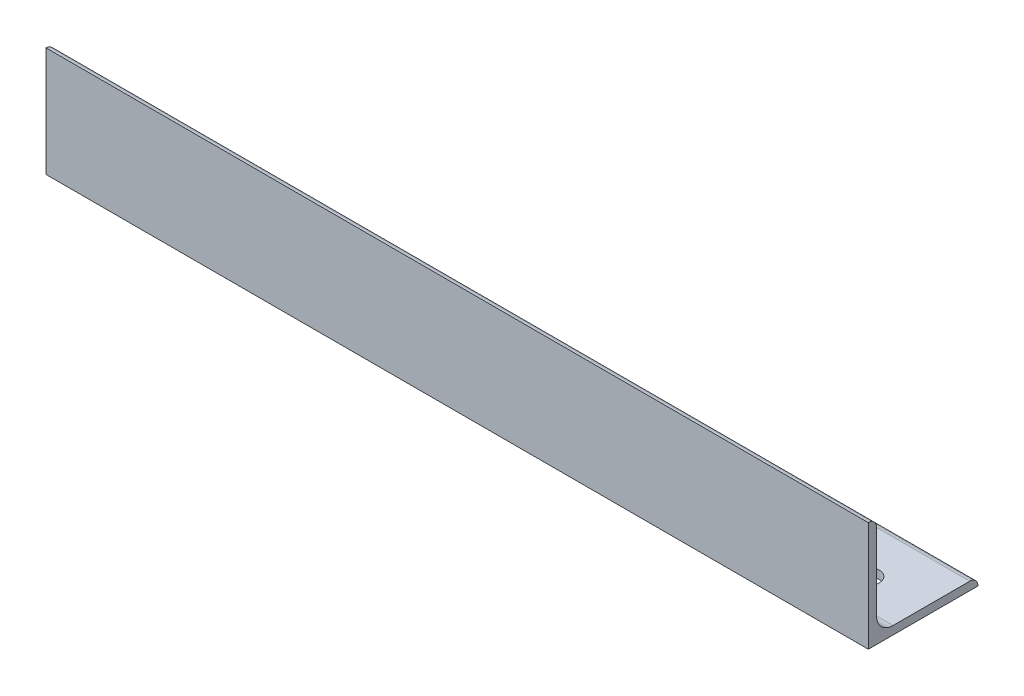
SolidWorks part; units mm, degrees
ref_plane "Front Plane" through (0, 0, 0) normal (0, 0, 1) x (1, 0, 0)
ref_plane "Top Plane" through (0, 0, 0) normal (0, 1, 0) x (1, 0, 0)
ref_plane "Right Plane" through (0, 0, 0) normal (1, 0, 0) x (0, 0, -1)
sketch "Sketch1" plane through (0, 0, 0) normal (0, 1, 0) x (1, 0, 0)
  line L0 (0, 0) -> (300, 0)
  dimension "D1" = 300
other "L angle (equal) 40X40X3(3)"
ref_plane "Plane1" through (0, 0, 0) normal (1, 0, 0) x (0, 0, -1)
sketch "Sketch13" plane through (0, 0, 0) normal (1, 0, 0) x (0, 0, -1)
  line L0 (0, 40) -> (0, 0)
  line L2 (3, 37) -> (3, 9)
  line L3 (9, 3) -> (37, 3)
  line L5 (40, 0) -> (0, 0)
  arc A0 (3, 37) -> (0, 40) centre (0, 37) ccw
  arc A1 (40, 0) -> (37, 3) centre (37, 0) ccw
  arc A2 (9, 3) -> (3, 9) centre (9, 9) cw
  point P8 (0, 20)
  point P9 (20, 0)
  point P10 (0, 0)
  dimension "Radius_2" = 3
  dimension "Radius_1" = 6
  dimension "V_leg" = 40
  dimension "H_leg" = 40
  dimension "thickness" = 3
ref_plane "Plane2" through (0, 0, 0) normal (0, -1, 0) x (-1, 0, 0)
sketch "Sketch14" plane through (0, 0, 0) normal (0, -1, 0) x (-1, 0, 0)
  line L0 (-280, 40) -> (-280, 0) construction
  line L1 (-20, 0) -> (-20, 40) construction
  line L4 (0, 0) -> (0, 40)
  line L5 (0, 40) -> (-300, 40)
  line L6 (-300, 40) -> (-300, 0)
  line L7 (-300, 0) -> (0, 0)
  line L8 (0, 0) -> (0, 40) construction
  line L9 (0, 40) -> (-300, 40) construction
  line L10 (-300, 40) -> (-300, 0) construction
  line L11 (-300, 0) -> (0, 0) construction
  circle A0 centre (-280, 20) radius 4
  circle A1 centre (-20, 20) radius 4
  dimension "D1" = 0
  dimension "D2" = 20
extrude "Cut-Extrude1" cut sketch "Sketch14" against normal blind 10
